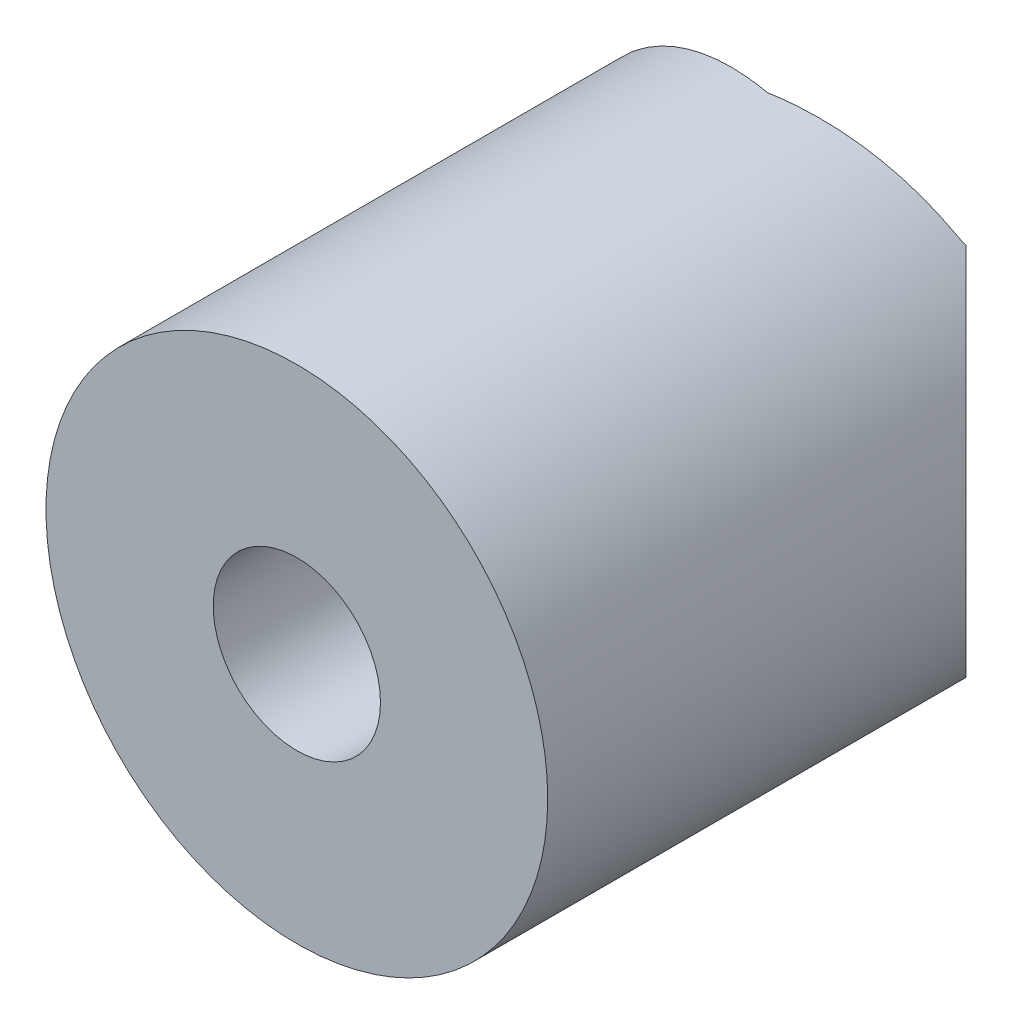
SolidWorks part; units mm, degrees
material "Ceramic Insulation"
ref_plane "Front Plane" through (0, 0, 0) normal (0, 0, 1) x (1, 0, 0)
ref_plane "Top Plane" through (0, 0, 0) normal (0, 1, 0) x (1, 0, 0)
ref_plane "Right Plane" through (0, 0, 0) normal (1, 0, 0) x (0, 0, -1)
sketch "Sketch1" plane through (0, 0, 0) normal (0, 0, 1) x (1, 0, 0)
  circle A0 centre (0, 0) radius 12.7
  circle A1 centre (0, 0) radius 38.1
  dimension "D2" = 25.4
  dimension "D1" = 25.4
extrude "Boss-Extrude1" add sketch "Sketch1" against normal blind 76.2
sketch "Sketch2" plane through (0, 0, 0) normal (0, 1, 0) x (1, 0, 0)
  line L0 (0, 76.2) -> (0, 0) construction
  line L1 (12.7, 76.2) -> (-12.7, 76.2) construction
  line L2 (-25.4, 76.2) -> (-38.1, 63.5)
  line L3 (38.1, 76.2) -> (-38.1, 76.2) construction
  line L4 (-38.1, 76.2) -> (-38.1, 0) construction
  line L5 (-38.1, 63.5) -> (-38.1, 76.2)
  line L6 (-38.1, 76.2) -> (-25.4, 76.2)
  line L7 (0, 71.4756) -> (-24.3398, 75.8836)
  line L8 (-28.4472, 80.6756) -> (28.4472, 80.6756) construction
  line L9 (0, 80.6756) -> (0, 71.4756) construction
  line L10 (-25.4, 76.2) -> (25.4, 76.2)
  line L11 (0, 76.2) -> (0, 71.4756)
  line L12 (0, 71.4756) -> (24.3398, 75.8836)
  line L13 (38.1, 76.2) -> (25.4, 76.2)
  line L14 (38.1, 63.5) -> (38.1, 76.2)
  line L15 (25.4, 76.2) -> (38.1, 63.5)
  arc A0 (-24.3398, 75.8836) -> (-25.4, 76.2) centre (-23.4488, 80.8036) cw
  arc A1 (-25.4, 76.2) -> (-28.4472, 80.6756) centre (-23.4488, 80.8036) cw construction
  arc A2 (25.4, 76.2) -> (28.4472, 80.6756) centre (23.4488, 80.8036) ccw construction
  arc A3 (24.3398, 75.8836) -> (25.4, 76.2) centre (23.4488, 80.8036) ccw
  dimension "D3" = 5
  dimension "D1" = 12.7
  dimension "D2" = 45
  dimension "D4" = 9.2
  dimension "D5" = 10.265
  dimension "D6" = 4.7244
extrude "Cut-Extrude1" cut sketch "Sketch2" against normal through all both and the other way through all contours L6 L5 L2 | A0 L7 L11 L10 | L12 A3 L10 L11 | L13 L15 L14
equation "\"ID\"= 1"
equation "\"D2@Sketch1\"=\"ID\""
equation "\"L\"= 4.5"
equation "\"D1@Boss-Extrude1\"=\"L\"-1.5"
equation "\"InsulationThickness\"= 1"
equation "\"D1@Sketch1\"=\"InsulationThickness\""
